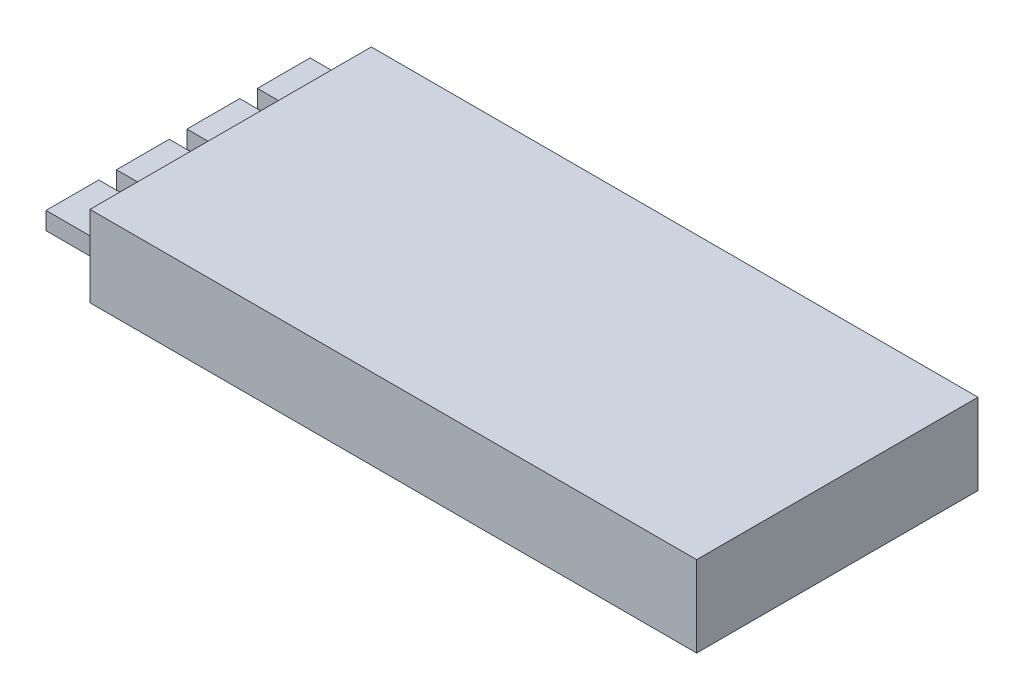
SolidWorks part; units mm, degrees
ref_plane "Front Plane" through (0, 0, 0) normal (0, 0, 1) x (1, 0, 0)
ref_plane "Top Plane" through (0, 0, 0) normal (0, 1, 0) x (1, 0, 0)
ref_plane "Right Plane" through (0, 0, 0) normal (1, 0, 0) x (0, 0, -1)
sketch "Sketch1" plane through (0, 0, 0) normal (0, 1, 0) x (1, 0, 0)
  line L1 (86.25, -40) -> (-86.25, -40)
  line L2 (86.25, -40) -> (86.25, 40)
  line L3 (86.25, 40) -> (-86.25, 40)
  line L4 (-86.25, -40) -> (-86.25, 40)
  line L5 (86.25, -40) -> (-86.25, 40) construction
  line L6 (86.25, 40) -> (-86.25, -40) construction
  point P0 (0, 0)
  dimension "D1" = 172.5
  dimension "D2" = 80
extrude "Boss-Extrude1" add sketch "Sketch1" along normal blind 23
sketch "Sketch2" plane through (-86.25, 0, 0) normal (-1, 0, 0) x (0, 0, 1)
  line L0 (40, 11.5) -> (-40, 11.5) construction
  line L1 (40, 23) -> (40, 0) construction
  line L2 (-40, 23) -> (-40, 0) construction
  line L3 (17.4651, 9) -> (17.4651, 14)
  line L4 (37.5, 9) -> (22.5, 9)
  line L5 (37.5, 9) -> (37.5, 14)
  line L6 (37.5, 14) -> (22.5, 14)
  line L7 (22.5, 9) -> (22.5, 14)
  line L8 (37.5, 9) -> (22.5, 14) construction
  line L9 (37.5, 14) -> (22.5, 9) construction
  line L10 (17.4651, 9) -> (2.4651, 9)
  line L11 (2.4651, 9) -> (2.4651, 14)
  line L12 (17.4651, 14) -> (2.4651, 14)
  line L13 (-2.5698, 9) -> (-2.5698, 14)
  line L14 (-2.5698, 9) -> (-17.5698, 9)
  line L15 (-17.5698, 9) -> (-17.5698, 14)
  line L16 (-2.5698, 14) -> (-17.5698, 14)
  line L17 (-22.6047, 9) -> (-22.6047, 14)
  line L18 (-22.6047, 9) -> (-37.6047, 9)
  line L19 (-37.6047, 9) -> (-37.6047, 14)
  line L20 (-22.6047, 14) -> (-37.6047, 14)
  point P6 (30, 11.5)
  dimension "D1" = 5
  dimension "D2" = 15
  dimension "D3" = 10
  dimension "D4" = 4
extrude "Boss-Extrude2" add sketch "Sketch2" along normal blind 15 contours L5 L4 L7 L6
